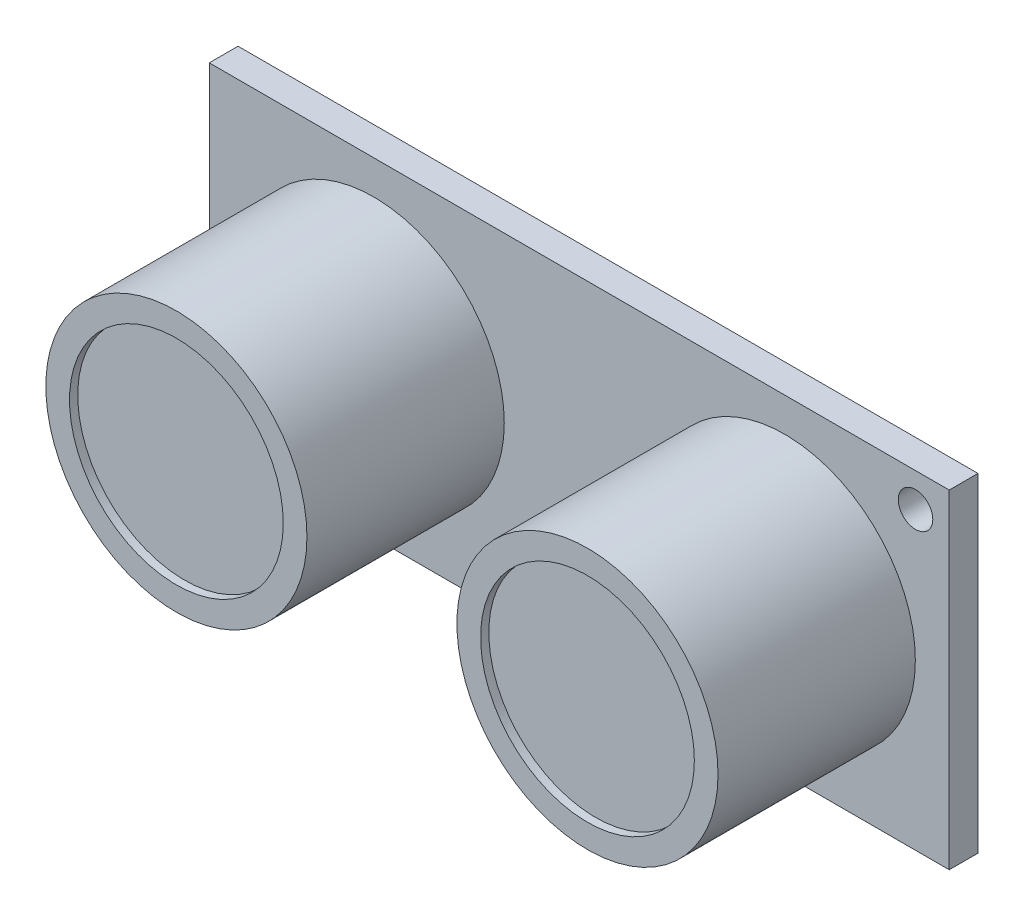
SolidWorks part; units mm, degrees
ref_plane "Front Plane" through (0, 0, 0) normal (0, 0, 1) x (1, 0, 0)
ref_plane "Top Plane" through (0, 0, 0) normal (0, 1, 0) x (1, 0, 0)
ref_plane "Right Plane" through (0, 0, 0) normal (1, 0, 0) x (0, 0, -1)
sketch "Sketch1" plane through (0, 0, 0) normal (0, 0, 1) x (1, 0, 0)
  line L1 (-60.6064, 25.474) -> (-15.6064, 25.474)
  line L2 (-60.6064, 25.474) -> (-60.6064, 5.474)
  line L3 (-60.6064, 5.474) -> (-15.6064, 5.474)
  line L4 (-15.6064, 25.474) -> (-15.6064, 5.474)
  circle A0 centre (-58.5564, 7.524) radius 1.05
  circle A1 centre (-17.6564, 23.424) radius 1.05
  dimension "D3" = 2.1
  dimension "D4" = 2.1
  dimension "D1" = 45
  dimension "D2" = 20
  dimension "D5" = 2.05
  dimension "D6" = 2.05
  dimension "D7" = 2.05
  dimension "D8" = 2.05
extrude "Boss-Extrude1" add sketch "Sketch1" along normal blind 1.75
sketch "Sketch2" plane through (0, 0, 1.75) normal (0, 0, 1) x (1, 0, 0)
  line L0 (-60.6064, 25.474) -> (-60.6064, 5.474) construction
  line L1 (-15.6064, 5.474) -> (-15.6064, 25.474) construction
  line L2 (-60.6064, 5.474) -> (-15.6064, 5.474) construction
  line L3 (-15.6064, 25.474) -> (-60.6064, 25.474) construction
  circle A0 centre (-50.6064, 15.474) radius 7.94
  circle A1 centre (-25.6064, 15.474) radius 7.94
  dimension "D1" = 15.88
  dimension "D2" = 15.88
  dimension "D3" = 10
  dimension "D4" = 10
  dimension "D5" = 10
  dimension "D6" = 10
extrude "Boss-Extrude2" add sketch "Sketch2" along normal blind 12
sketch "Sketch3" plane through (0, 0, 13.75) normal (0, 0, 1) x (1, 0, 0)
  circle A0 centre (-50.6064, 15.474) radius 6.5
  circle A1 centre (-25.6064, 15.474) radius 6.5
  circle A3 centre (-50.6064, 15.474) radius 7.94 construction
  circle A4 centre (-25.6064, 15.474) radius 7.94 construction
  dimension "D1" = 13
  dimension "D2" = 13
extrude "Cut-Extrude1" cut sketch "Sketch3" against normal blind 0.5
ref_plane "Plane1" through (-41.6464, 0, 0) normal (-1, 0, 0) x (0, 0, 1)
sketch "Sketch4" plane through (-41.6464, 0, 0) normal (-1, 0, 0) x (0, 0, 1)
  line L0 (3.5, 7.374) -> (-3.07, 7.374)
  line L1 (-4.07, 6.374) -> (-4.07, 0.944)
  line L2 (0, 25.474) -> (0, 5.474) construction
  line L3 (1.75, 25.474) -> (1.75, 5.474) construction
  line L4 (1.75, 5.474) -> (0, 5.474) construction
  arc A0 (-3.07, 7.374) -> (-4.07, 6.374) centre (-3.07, 6.374) ccw
  point P11 (-4.07, 7.374)
  dimension "D5" = 1
  dimension "D1" = 4.07
  dimension "D2" = 1.75
  dimension "D3" = 6.43
  dimension "D4" = 1.9
ref_plane "Plane2" through (0, 0.944, 0) normal (0, -1, 0) x (-1, 0, 0)
sketch "Sketch5" plane through (0, 0.944, 0) normal (0, -1, 0) x (-1, 0, 0)
  circle A0 centre (41.6464, 4.07) radius 0.32
  dimension "D1" = 0.64
sweep "Sweep1" add profiles "Sketch5" path "Sketch4"
fillet "Fillet1" radius 0.32 2 edges at (-41.6464, 0.944, -4.39) (-41.6464, 7.694, 3.5)
pattern_linear "LPattern1" count 4 spacing 2.54 along (1, 0, 0) of "Fillet1", "Sweep1"
sketch "Sketch6" plane through (0, 0, 0) normal (0, 0, -1) x (-1, 0, 0)
  line L1 (32.8933, 8.6949) -> (42.7535, 8.6949)
  line L2 (32.8933, 8.6949) -> (32.8933, 5.8735)
  line L3 (32.8933, 5.8735) -> (42.7535, 5.8735)
  line L4 (42.7535, 8.6949) -> (42.7535, 5.8735)
extrude "Boss-Extrude3" add sketch "Sketch6" along normal blind 2
equation "\"D6@Sketch1\"=\"D5@Sketch1\""
equation "\"D7@Sketch1\"=\"D5@Sketch1\""
equation "\"D8@Sketch1\"=\"D5@Sketch1\""
equation "\"D3@Sketch1\"=\"D4@Sketch1\""
equation "\"D2@Sketch2\"=\"D1@Sketch2\""
